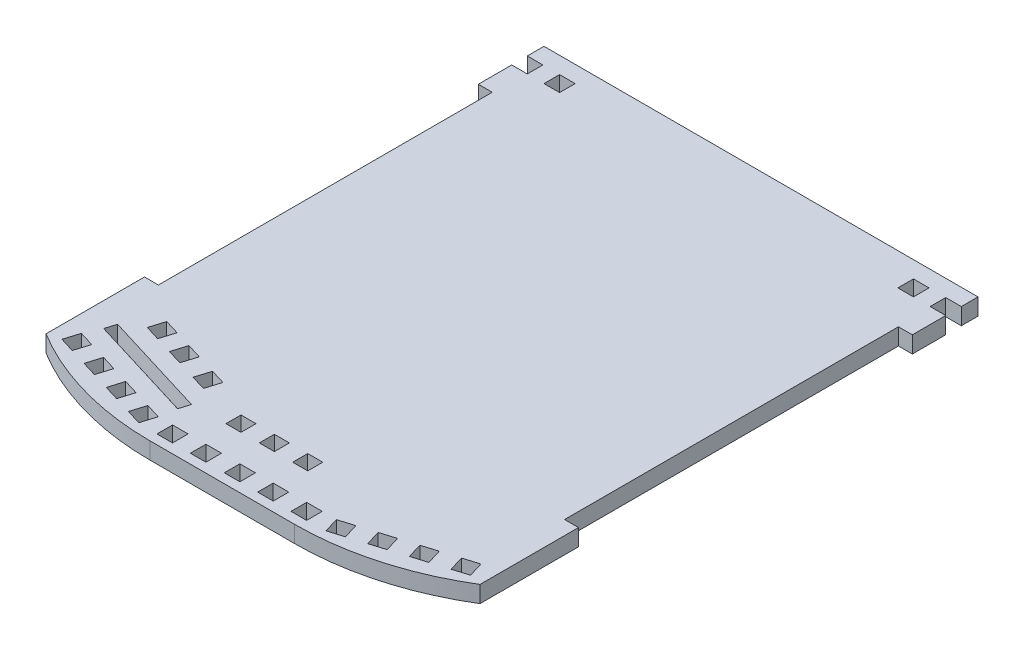
SolidWorks part; units mm, degrees
ref_plane "Front Plane" through (0, 0, 0) normal (0, 0, 1) x (1, 0, 0)
ref_plane "Top Plane" through (0, 0, 0) normal (0, 1, 0) x (1, 0, 0)
ref_plane "Right Plane" through (0, 0, 0) normal (1, 0, 0) x (0, 0, -1)
sketch "Sketch1" plane through (0, 0, 0) normal (0, 1, 0) x (1, 0, 0)
  line L36 (-37.8446, 15.0909) -> (-35.0446, 15.0909)
  line L37 (-37.8446, 18.0909) -> (40.1554, 18.0909)
  line L38 (-37.8446, 18.0909) -> (-37.8446, -51.4091)
  line L40 (40.1554, 18.0909) -> (40.1554, -51.4091)
  line L41 (-37.8446, 15.0909) -> (-37.8446, 12.2909)
  line L42 (-37.8446, 12.2909) -> (-35.0446, 12.2909)
  line L43 (-35.0446, 15.0909) -> (-35.0446, 12.2909)
  line L44 (-32.0446, 15.0909) -> (-29.2446, 15.0909)
  line L45 (-32.0446, 15.0909) -> (-32.0446, 12.2909)
  line L46 (-32.0446, 12.2909) -> (-29.2446, 12.2909)
  line L47 (-29.2446, 15.0909) -> (-29.2446, 12.2909)
  line L58 (1.1554, 18.0909) -> (1.1554, -78.7199) construction
  line L103 (67.2577, 50.7531) -> (67.2577, -169.2469) construction
  line L126 (-11.8131, -78.7199) -> (14.1238, -78.7199)
  line L127 (1.1554, -78.7199) -> (11.1554, -78.7199)
  line L128 (1.1554, -78.7199) -> (-8.8446, -78.7199)
  line L196 (-11.8131, -78.7199) -> (11.1554, -78.7199)
  line L197 (34.3554, 15.0909) -> (34.3554, 12.2909)
  line L198 (7.0054, -69.2199) -> (4.3054, -69.2199)
  line L235 (5.8054, -74.2199) -> (8.6054, -74.2199)
  line L236 (-0.1946, -74.2199) -> (2.6054, -74.2199)
  line L237 (-0.1946, -74.2199) -> (-0.1946, -77.0199)
  line L238 (-0.1946, -77.0199) -> (2.6054, -77.0199)
  line L239 (2.6054, -74.2199) -> (2.6054, -77.0199)
  line L240 (5.8054, -74.2199) -> (5.8054, -77.0199)
  line L241 (5.8054, -77.0199) -> (8.6054, -77.0199)
  line L242 (8.6054, -74.2199) -> (8.6054, -77.0199)
  line L243 (11.8054, -74.2199) -> (14.6054, -74.2199)
  line L244 (11.8054, -74.2199) -> (11.8054, -77.0199)
  line L245 (11.8054, -77.0199) -> (14.6054, -77.0199)
  line L246 (14.6054, -74.2199) -> (14.6054, -77.0199)
  line L247 (-9.4946, -74.2199) -> (-9.4946, -77.0199)
  line L248 (-9.4946, -77.0199) -> (-12.2946, -77.0199)
  line L249 (-12.2946, -74.2199) -> (-12.2946, -77.0199)
  line L250 (-9.4946, -74.2199) -> (-12.2946, -74.2199)
  line L251 (-3.4946, -74.2199) -> (-3.4946, -77.0199)
  line L252 (-3.4946, -77.0199) -> (-6.2946, -77.0199)
  line L253 (-6.2946, -74.2199) -> (-6.2946, -77.0199)
  line L254 (-3.4946, -74.2199) -> (-6.2946, -74.2199)
  line L255 (-37.8446, -53.7199) -> (-37.8446, -71.4091) construction
  line L256 (40.1554, -53.7199) -> (40.1554, -71.4091) construction
  line L257 (7.0054, -69.2199) -> (7.0054, -66.5199)
  line L258 (-29.0112, -69.9038) -> (-26.3336, -70.7224)
  line L259 (-34.7491, -68.1496) -> (-32.0714, -68.9682)
  line L260 (7.0054, -66.5199) -> (4.3054, -66.5199)
  line L261 (4.3054, -69.2199) -> (4.3054, -66.5199)
  line L262 (1.0054, -69.2199) -> (-1.6946, -69.2199)
  line L263 (1.0054, -69.2199) -> (1.0054, -66.5199)
  line L264 (1.0054, -66.5199) -> (-1.6946, -66.5199)
  line L265 (-1.6946, -69.2199) -> (-1.6946, -66.5199)
  line L266 (-4.9946, -69.2199) -> (-7.6946, -69.2199)
  line L267 (-4.9946, -69.2199) -> (-4.9946, -66.5199)
  line L268 (-4.9946, -66.5199) -> (-7.6946, -66.5199)
  line L269 (-7.6946, -69.2199) -> (-7.6946, -66.5199)
  line L270 (-34.7491, -68.1496) -> (-35.5677, -70.8272)
  line L271 (-35.5677, -70.8272) -> (-32.8901, -71.6459)
  line L272 (-32.0714, -68.9682) -> (-32.8901, -71.6459)
  line L273 (-29.0112, -69.9038) -> (-29.8299, -72.5814)
  line L274 (-29.8299, -72.5814) -> (-27.1522, -73.4001)
  line L275 (-26.3336, -70.7224) -> (-27.1522, -73.4001)
  line L276 (-23.3416, -66.4087) -> (-23.9264, -68.3213) construction
  line L277 (-32.9047, -63.485) -> (-13.7786, -69.3324)
  line L278 (-32.9047, -63.485) -> (-33.4894, -65.3976)
  line L279 (-33.4894, -65.3976) -> (-14.3633, -71.245)
  line L280 (-13.7786, -69.3324) -> (-14.3633, -71.245)
  line L281 (-20.5958, -72.4767) -> (-21.4144, -75.1543)
  line L282 (-21.4144, -75.1543) -> (-24.0921, -74.3357)
  line L283 (-23.2734, -71.658) -> (-24.0921, -74.3357)
  line L284 (-20.5958, -72.4767) -> (-23.2734, -71.658)
  line L285 (-15.6766, -76.9085) -> (-18.3542, -76.0899)
  line L286 (-17.5356, -73.4123) -> (-18.3542, -76.0899)
  line L287 (-14.8579, -74.2309) -> (-17.5356, -73.4123)
  line L288 (-14.8579, -74.2309) -> (-15.6766, -76.9085)
  line L289 (-23.176, -60.3943) -> (-20.4983, -61.213)
  line L290 (-23.176, -60.3943) -> (-23.9946, -63.072)
  line L291 (-23.9946, -63.072) -> (-21.317, -63.8906)
  line L292 (-20.4983, -61.213) -> (-21.317, -63.8906)
  line L293 (-28.9138, -58.6401) -> (-26.2361, -59.4588)
  line L294 (-28.9138, -58.6401) -> (-29.7324, -61.3178)
  line L295 (-29.7324, -61.3178) -> (-27.0548, -62.1364)
  line L296 (-26.2361, -59.4588) -> (-27.0548, -62.1364)
  line L297 (-14.378, -63.0842) -> (-15.1966, -65.7618)
  line L298 (-15.1966, -65.7618) -> (-17.8743, -64.9432)
  line L299 (-17.0556, -62.2655) -> (-17.8743, -64.9432)
  line L300 (-14.378, -63.0842) -> (-17.0556, -62.2655)
  line L301 (17.1686, -74.2309) -> (17.9873, -76.9085)
  line L302 (17.1686, -74.2309) -> (19.8463, -73.4123)
  line L303 (19.8463, -73.4123) -> (20.6649, -76.0899)
  line L304 (17.9873, -76.9085) -> (20.6649, -76.0899)
  line L305 (22.9065, -72.4767) -> (25.5841, -71.658)
  line L306 (25.5841, -71.658) -> (26.4028, -74.3357)
  line L307 (23.7251, -75.1543) -> (26.4028, -74.3357)
  line L308 (22.9065, -72.4767) -> (23.7251, -75.1543)
  line L309 (31.3219, -69.9038) -> (32.1406, -72.5814)
  line L310 (32.1406, -72.5814) -> (29.4629, -73.4001)
  line L311 (28.6443, -70.7224) -> (29.4629, -73.4001)
  line L312 (31.3219, -69.9038) -> (28.6443, -70.7224)
  line L313 (37.0598, -68.1496) -> (37.8784, -70.8272)
  line L314 (37.8784, -70.8272) -> (35.2008, -71.6459)
  line L315 (34.3821, -68.9682) -> (35.2008, -71.6459)
  line L316 (37.0598, -68.1496) -> (34.3821, -68.9682)
  line L317 (-37.8446, -71.4091) -> (-37.8446, -51.4091)
  line L318 (40.1554, -71.4091) -> (40.1554, -51.4091)
  line L320 (34.3554, 12.2909) -> (31.5554, 12.2909)
  line L321 (31.5554, 15.0909) -> (31.5554, 12.2909)
  line L322 (34.3554, 15.0909) -> (31.5554, 15.0909)
  line L323 (40.1554, 15.0909) -> (40.1554, 12.2909)
  line L324 (40.1554, 12.2909) -> (37.3554, 12.2909)
  line L325 (37.3554, 15.0909) -> (37.3554, 12.2909)
  line L326 (40.1554, 15.0909) -> (37.3554, 15.0909)
  line L327 (40.1554, -53.7091) -> (37.6554, -53.7091)
  line L328 (-37.8446, 6.2909) -> (-35.3446, 6.2909)
  line L329 (-37.8446, 6.2909) -> (-37.8446, -53.7091)
  line L330 (-37.8446, -53.7091) -> (-35.3446, -53.7091)
  line L331 (-35.3446, 6.2909) -> (-35.3446, -53.7091)
  line L332 (37.6554, 6.2909) -> (37.6554, -53.7091)
  line L333 (40.1554, 6.2909) -> (37.6554, 6.2909)
  line L334 (40.1554, 6.2909) -> (40.1554, -53.7091)
  line L335 (-49.4215, -93.388) -> (-4.4215, -93.388)
  line L336 (-49.4215, -93.388) -> (-49.4215, -95.388)
  line L337 (-49.4215, -95.388) -> (-4.4215, -95.388)
  line L338 (-4.4215, -93.388) -> (-4.4215, -95.388)
  line L339 (-32.9215, -90.2608) -> (-20.9215, -90.2608)
  line L340 (-32.9215, -90.2608) -> (-32.9215, -93.2608)
  line L341 (-32.9215, -93.2608) -> (-20.9215, -93.2608)
  line L342 (-20.9215, -90.2608) -> (-20.9215, -93.2608)
  arc A4 (-11.8131, -78.7199) -> (-37.8446, -71.4091) centre (-11.8131, -28.7199) cw
  arc A5 (14.1238, -78.7199) -> (40.1554, -71.4091) centre (14.1238, -28.7199) ccw
  dimension "D1" = 78
  dimension "D3" = 2.8
  dimension "D4" = 2.8
  dimension "D5" = 3
  dimension "D6" = 0
  dimension "D7" = 2.8
  dimension "D8" = 2.8
  dimension "D9" = 3
  dimension "D10" = 3
  dimension "D11" = 60
  dimension "D12" = 63.7
  dimension "D13" = 2.5
  dimension "D14" = 6
  dimension "D15" = 0
  dimension "D16" = 10
  dimension "D25" = 10
  dimension "D27" = 220
  dimension "D28" = 20
  dimension "D29" = 2.8
  dimension "D30" = 2.8
  dimension "D32" = 3.2
  dimension "D33" = 2.8
  dimension "D34" = 3.2
  dimension "D35" = 2.8
  dimension "D36" = 2.8
  dimension "D37" = 2.8
  dimension "D38" = 0
  dimension "D39" = 1.7
  dimension "D40" = 2.7
  dimension "D41" = 2.7
  dimension "D42" = 2.7
  dimension "D43" = 2.7
  dimension "D44" = 2.7
  dimension "D45" = 2.7
  dimension "D46" = 3.3
  dimension "D47" = 3.3
  dimension "D48" = 5
  dimension "D49" = 2.8
  dimension "D50" = 2.8
  dimension "D51" = 2
  dimension "D52" = 20
  dimension "D53" = 2.8
  dimension "D54" = 2.8
  dimension "D55" = 3.2
  dimension "D56" = 0
  dimension "D57" = 3
  dimension "D58" = 3.2
  dimension "D59" = 2.8
  dimension "D60" = 2.8
  dimension "D61" = 1.6
  dimension "D62" = 3
  dimension "D63" = 2.8
  dimension "D64" = 2.8
  dimension "D65" = 3
  dimension "D66" = 3.2
  dimension "D67" = 20
extrude "Boss-Extrude1" add sketch "Sketch1" along normal blind 3
